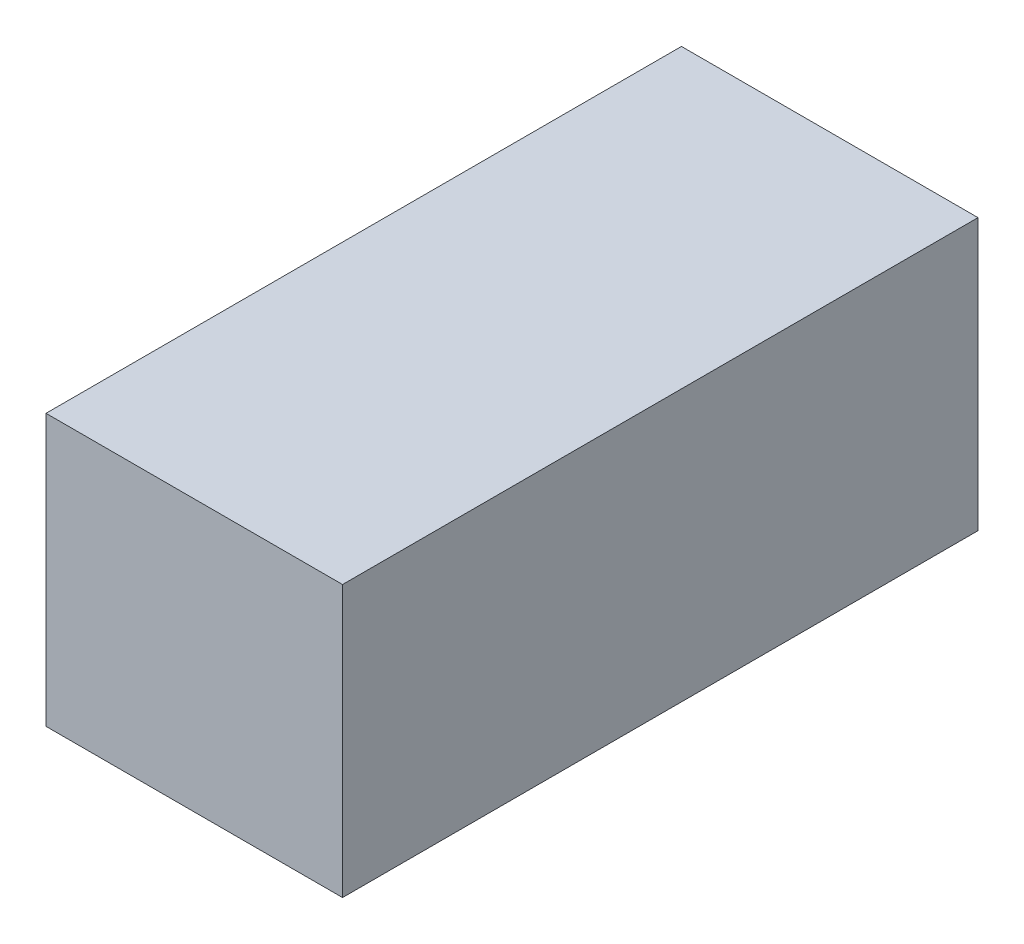
SolidWorks part; units mm, degrees
ref_plane "Спереди" through (0, 0, 0) normal (0, 0, 1) x (1, 0, 0)
ref_plane "Сверху" through (0, 0, 0) normal (0, 1, 0) x (1, 0, 0)
ref_plane "Справа" through (0, 0, 0) normal (1, 0, 0) x (0, 0, -1)
ref_plane "Плоскость4" through (0, 17, 0) normal (0, 1, 0) x (1, 0, 0)
sketch "Эскиз1" plane through (0, 17, 0) normal (0, 1, 0) x (1, 0, 0)
  line L0 (-17.5, -75) -> (17.5, -75)
  line L1 (17.5, -75) -> (17.5, 0)
  line L2 (17.5, 0) -> (-17.5, 0)
  line L3 (-17.5, 0) -> (-17.5, -75)
  dimension "D1" = 35
  dimension "D2" = 75
extrude "Бобышка-Вытянуть1" add sketch "Эскиз1" against normal blind 32
